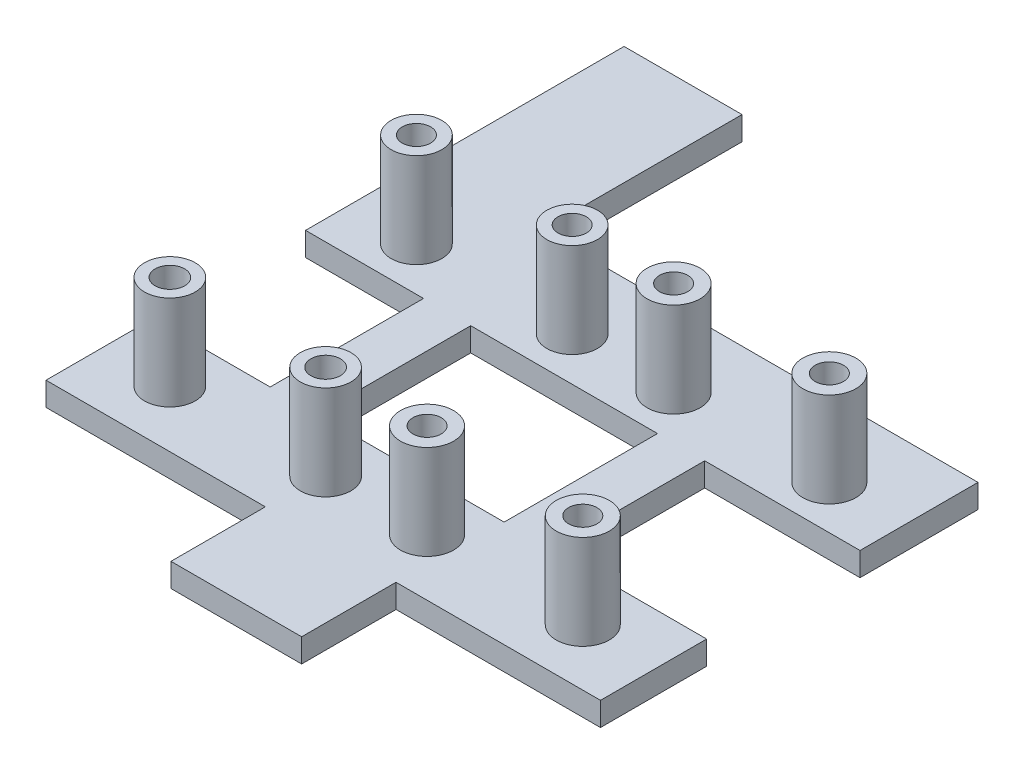
SolidWorks part; units mm, degrees
ref_plane "Front Plane" through (0, 0, 0) normal (0, 0, 1) x (1, 0, 0)
ref_plane "Top Plane" through (0, 0, 0) normal (0, 1, 0) x (1, 0, 0)
ref_plane "Right Plane" through (0, 0, 0) normal (1, 0, 0) x (0, 0, -1)
sketch "Sketch1" plane through (0, 0, 0) normal (0, 1, 0) x (1, 0, 0)
  line L1 (-30, 36) -> (30, 36)
  line L2 (-30, 36) -> (-30, -36)
  line L3 (-30, -36) -> (30, -36)
  line L4 (30, 36) -> (30, -36)
  line L5 (-30, 36) -> (30, -36) construction
  line L6 (-30, -36) -> (30, 36) construction
  point P0 (0, 0)
  dimension "D1" = 72
  dimension "D2" = 60
extrude "Bottom" add sketch "Sketch1" along normal blind 2
sketch "Sketch2" plane through (0, 2, 0) normal (0, 1, 0) x (1, 0, 0)
  line L1 (-23, -10.8) -> (28, -10.8) construction
  line L2 (-23, -10.8) -> (-23, -33.8) construction
  line L3 (-23, -33.8) -> (28, -33.8) construction
  line L4 (28, -10.8) -> (28, -33.8) construction
  line L6 (-30, -36) -> (30, -36) construction
  line L7 (28, -22.3) -> (-23, -22.3) construction
  line L8 (28, -10.8) -> (25.7, -10.8) construction
  line L9 (28, -10.8) -> (28, -13.1) construction
  line L10 (28, -13.1) -> (25.7, -13.1) construction
  line L11 (25.7, -10.8) -> (25.7, -13.1) construction
  line L12 (30, -36) -> (30, 36) construction
  line L14 (2.5, -10.8) -> (2.5, -33.8) construction
  circle A1 centre (25.7, -13.1) radius 2.25
  circle A2 centre (-20.7, -13.1) radius 2.25
  circle A3 centre (25.7, -31.5) radius 2.25
  circle A4 centre (-20.7, -31.5) radius 2.25
  point P26 (-24.7, -31.65)
  dimension "D8" = 4.5
  dimension "D1" = 51
  dimension "D2" = 23
  dimension "D3" = 2
  dimension "D5" = 2.2
  dimension "D6" = 2.3
  dimension "D7" = 2.3
extrude "Pin Locs" add sketch "Sketch2" along normal blind 4
sketch "Sketch5" plane through (0, 6, 0) normal (0, 1, 0) x (1, 0, 0)
  circle A0 centre (-20.7, -31.5) radius 1.25
  circle A1 centre (-20.7, -13.1) radius 1.25
  circle A2 centre (25.7, -13.1) radius 1.25
  circle A3 centre (25.7, -31.5) radius 1.25
  dimension "D1" = 2.5
extrude "Pin Holes" cut sketch "Sketch5" against normal blind 4
sketch "Sketch3" plane through (0, 2, 0) normal (0, 1, 0) x (1, 0, 0)
  line L0 (1.2, -3.5) -> (-16.6, -3.5) construction
  line L1 (23, -3.5) -> (5.2, -3.5) construction
  line L2 (23, -3.5) -> (23, 22) construction
  line L3 (23, 22) -> (5.2, 22) construction
  line L4 (5.2, -3.5) -> (5.2, 22) construction
  line L5 (1.2, -3.5) -> (1.2, 22) construction
  line L6 (1.2, 22) -> (-16.6, 22) construction
  line L7 (-16.6, -3.5) -> (-16.6, 22) construction
  line L8 (30, -36) -> (30, 36) construction
  line L9 (30, 36) -> (-30, 36) construction
  line L10 (14.1, 22) -> (14.1, -3.5) construction
  line L11 (5.2, 9.25) -> (23, 9.25) construction
  line L12 (-7.7, 22) -> (-7.7, -3.5) construction
  line L13 (-16.6, 9.25) -> (1.2, 9.25) construction
  line L14 (-14.3, -1.2) -> (-1.1, -1.2) construction
  line L15 (23, 22) -> (20.7, 22) construction
  line L16 (23, 22) -> (23, 19.7) construction
  line L17 (23, 19.7) -> (20.7, 19.7) construction
  line L18 (20.7, 22) -> (20.7, 19.7) construction
  line L19 (1.2, 22) -> (-1.1, 22) construction
  line L20 (1.2, 22) -> (1.2, 19.7) construction
  line L21 (1.2, 19.7) -> (-1.1, 19.7) construction
  line L22 (-1.1, 22) -> (-1.1, 19.7) construction
  line L23 (7.5, -1.2) -> (20.7, -1.2) construction
  circle A0 centre (20.7, 19.7) radius 2.25
  circle A1 centre (20.7, -1.2) radius 2.25
  circle A2 centre (7.5, -1.2) radius 2.25
  circle A3 centre (7.5, 19.7) radius 2.25
  circle A4 centre (-1.1, 19.7) radius 2.15
  circle A5 centre (-1.1, -1.2) radius 2.15
  circle A6 centre (-14.3, -1.2) radius 2.15
  circle A7 centre (-14.3, 19.7) radius 2.15
  dimension "D10" = 4.5
  dimension "D13" = 4.3
  dimension "D2" = 17.8
  dimension "D3" = 17.8
  dimension "D4" = 25.5
  dimension "D5" = 7
  dimension "D6" = 14
  dimension "D7" = 4
  dimension "D8" = 2.3
  dimension "D9" = 2.3
  dimension "D11" = 2.3
  dimension "D12" = 2.3
extrude "Sensor Pins" add sketch "Sketch3" along normal blind 8
sketch "Sketch6" plane through (0, 10, 0) normal (0, 1, 0) x (1, 0, 0)
  circle A0 centre (-14.3, -1.2) radius 1.25
  circle A1 centre (-1.1, -1.2) radius 1.25
  circle A2 centre (-1.1, 19.7) radius 1.2
  circle A3 centre (-14.3, 19.7) radius 1.2
  circle A6 centre (20.7, -1.2) radius 1.2
  circle A7 centre (20.7, 19.7) radius 1.2
  circle A8 centre (7.5, 19.7) radius 1.2
  circle A9 centre (7.5, -1.2) radius 1.2
  dimension "D1" = 2.5
extrude "Pin Holes Sensors" cut sketch "Sketch6" against normal blind 4
sketch "Sketch4" plane through (0, 2, 0) normal (0, 1, 0) x (1, 0, 0)
  line L1 (30, 36) -> (22, 36)
  line L2 (30, 36) -> (30, 26)
  line L3 (30, 26) -> (22, 26)
  line L4 (22, 36) -> (22, 26)
  dimension "D1" = 10
  dimension "D2" = 8
extrude "Power Cable" cut sketch "Sketch4" against normal blind 2
sketch "Sketch7" plane through (0, 2, 0) normal (0, 1, 0) x (1, 0, 0)
  line L0 (-30, 36) -> (-30, -36) construction
  line L1 (-16, -8) -> (0.5, -8)
  line L2 (-16, -8) -> (-16, -33)
  line L3 (-16, -33) -> (0.5, -33)
  line L4 (0.5, -8) -> (0.5, -33)
  line L5 (-27, 16) -> (-10, 16)
  line L6 (-27, 16) -> (-27, 3)
  line L7 (-27, 3) -> (-10, 3)
  line L8 (-10, 16) -> (-10, 3)
  line L9 (30, -36) -> (30, 26) construction
  line L10 (-30, -36) -> (30, -36) construction
  line L11 (22, 36) -> (-30, 36) construction
  line L18 (-6, 16) -> (9.834, 16)
  line L19 (-6, 16) -> (-6, 3)
  line L20 (-6, 3) -> (9.834, 3)
  line L21 (9.834, 16) -> (9.834, 3)
  line L22 (13.834, 16) -> (27, 16)
  line L23 (13.834, 16) -> (13.834, 3)
  line L24 (13.834, 3) -> (27, 3)
  line L25 (27, 16) -> (27, 3)
  line L26 (4.5, -8) -> (20, -8)
  line L27 (4.5, -8) -> (4.5, -33)
  line L28 (4.5, -33) -> (20, -33)
  line L29 (20, -8) -> (20, -33)
  dimension "D1" = 14
  dimension "D2" = 29.5
  dimension "D3" = 3
  dimension "D4" = 44
  dimension "D5" = 11
  dimension "D6" = 20
  dimension "D7" = 40
  dimension "D8" = 3
  dimension "D13" = 4
  dimension "D14" = 4
  dimension "D15" = 3
  dimension "D16" = 10
  dimension "D17" = 4
extrude "Cut-Extrude1" cut sketch "Sketch7" against normal blind 2
sketch "Sketch8" plane through (0, 0, 36) normal (0, 0, 1) x (1, 0, 0)
  line L1 (-32.5788, -3.2826) -> (32.4032, -3.2826)
  line L2 (-32.5788, -3.2826) -> (-32.5788, 15.2683)
  line L3 (-32.5788, 15.2683) -> (32.4032, 15.2683)
  line L4 (32.4032, -3.2826) -> (32.4032, 15.2683)
extrude "Cut-Extrude2" cut sketch "Sketch8" against normal blind 30
sketch "Sketch9" plane through (0, 0, -36) normal (0, 0, -1) x (-1, 0, 0)
  line L1 (-34.0085, -6.0527) -> (32.6482, -6.0527)
  line L2 (-34.0085, -6.0527) -> (-34.0085, 15.319)
  line L3 (-34.0085, 15.319) -> (32.6482, 15.319)
  line L4 (32.6482, -6.0527) -> (32.6482, 15.319)
extrude "Cut-Extrude3" cut sketch "Sketch9" against normal blind 10
sketch "Sketch10" plane through (-30, 0, 0) normal (-1, 0, 0) x (0, 0, 1)
  line L1 (-27.7623, -3.5274) -> (9.1793, -3.5274)
  line L2 (-27.7623, -3.5274) -> (-27.7623, 13.5447)
  line L3 (-27.7623, 13.5447) -> (9.1793, 13.5447)
  line L4 (9.1793, -3.5274) -> (9.1793, 13.5447)
extrude "Cut-Extrude4" cut sketch "Sketch10" against normal blind 10
sketch "Sketch12" plane through (30, 0, 0) normal (1, 0, 0) x (0, 0, -1)
  line L1 (-10.1044, -4.381) -> (28.0042, -4.381)
  line L2 (-10.1044, -4.381) -> (-10.1044, 13.7187)
  line L3 (-10.1044, 13.7187) -> (28.0042, 13.7187)
  line L4 (28.0042, -4.381) -> (28.0042, 13.7187)
extrude "Cut-Extrude5" cut sketch "Sketch12" against normal blind 3
sketch "Sketch13" plane through (0, 0, -26) normal (0, 0, -1) x (-1, 0, 0)
  line L0 (20, 0) -> (-27, 0) construction
  line L1 (20, 0) -> (10, 0)
  line L2 (20, 0) -> (20, 2)
  line L3 (20, 2) -> (10, 2)
  line L4 (10, 0) -> (10, 2)
  line L5 (20, 0) -> (20, 2) construction
  line L6 (20, 2) -> (-27, 2) construction
  dimension "D1" = 10
extrude "Boss-Extrude1" add sketch "Sketch13" along normal blind 17
sketch "Sketch14" plane through (0, 0, 6) normal (0, 0, 1) x (1, 0, 0)
  line L0 (27, 0) -> (-20, 0) construction
  line L1 (-1.4074, 0) -> (9.6693, 0)
  line L2 (-1.4074, 0) -> (-1.4074, 2)
  line L3 (-1.4074, 2) -> (9.6693, 2)
  line L4 (9.6693, 0) -> (9.6693, 2)
  line L5 (27, 2) -> (-20, 2) construction
extrude "Boss-Extrude2" add sketch "Sketch14" along normal blind 8
